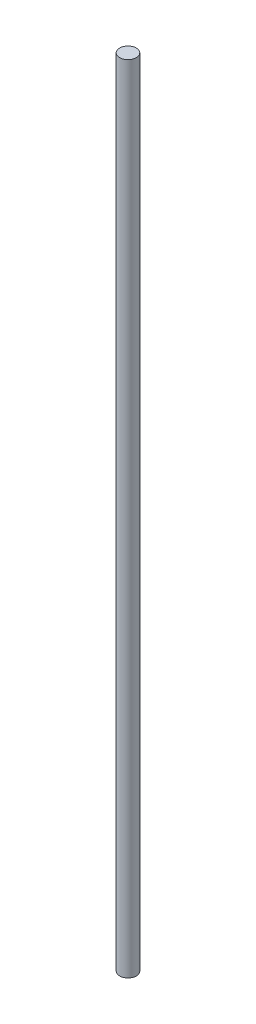
SolidWorks part; units mm, degrees
ref_plane "Front Plane" through (0, 0, 0) normal (0, 0, 1) x (1, 0, 0)
ref_plane "Top Plane" through (0, 0, 0) normal (0, 1, 0) x (1, 0, 0)
ref_plane "Right Plane" through (0, 0, 0) normal (1, 0, 0) x (0, 0, -1)
sketch "Sketch1" plane through (0, 0, 0) normal (0, 1, 0) x (1, 0, 0)
  circle A0 centre (0, 0) radius 1.5
  dimension "D1" = 3
extrude "Boss-Extrude1" add sketch "Sketch1" along normal blind 143
